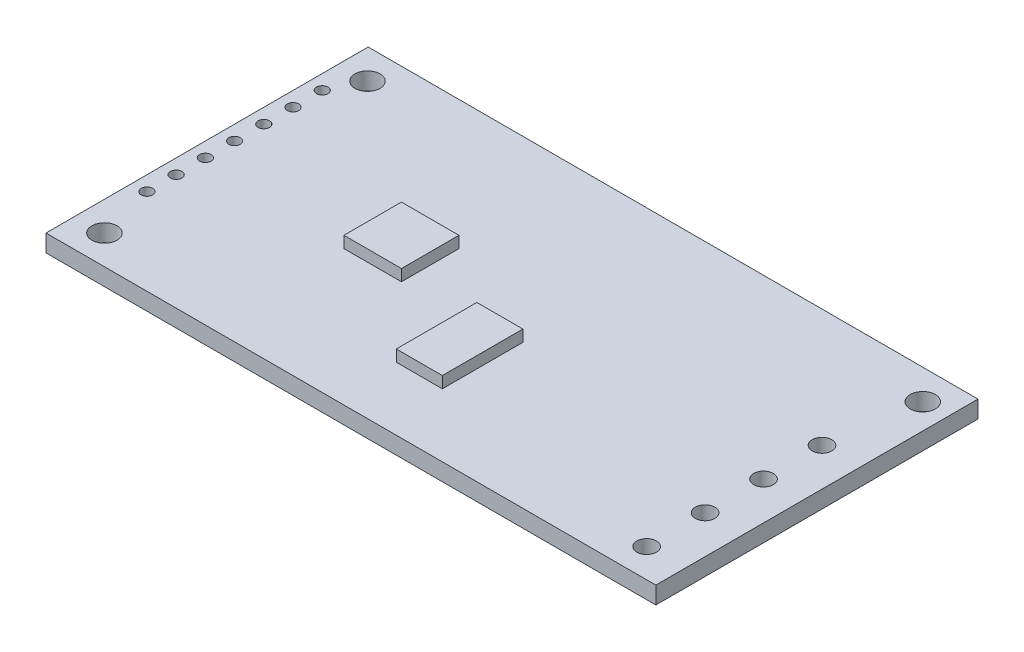
SolidWorks part; units mm, degrees
material "A-Glass Fiber"
ref_plane "Front Plane" through (0, 0, 0) normal (0, 0, 1) x (1, 0, 0)
ref_plane "Top Plane" through (0, 0, 0) normal (0, 1, 0) x (1, 0, 0)
ref_plane "Right Plane" through (0, 0, 0) normal (1, 0, 0) x (0, 0, -1)
sketch "Sketch1" plane through (0, 0, 0) normal (0, 1, 0) x (1, 0, 0)
  line L1 (-26.5, -14) -> (26.5, -14)
  line L2 (-26.5, -14) -> (-26.5, 14)
  line L3 (-26.5, 14) -> (26.5, 14)
  line L4 (26.5, -14) -> (26.5, 14)
  line L5 (-26.5, -14) -> (26.5, 14) construction
  line L6 (-26.5, 14) -> (26.5, -14) construction
  point P0 (0, 0)
  dimension "D1" = 53
  dimension "D2" = 28
extrude "Boss-Extrude1" add sketch "Sketch1" along normal blind 1.5
sketch "Sketch2" plane through (0, 1.5, 0) normal (0, 1, 0) x (1, 0, 0)
  line L0 (-26.5, 14) -> (-26.5, -14) construction
  line L1 (-26.5, -14) -> (26.5, -14) construction
  circle A0 centre (-23.96, -11.46) radius 1.0922
  dimension "D1" = 2.1844
  dimension "D2" = 2.54
  dimension "D3" = 2.54
extrude "Cut-Extrude1" cut sketch "Sketch2" against normal through all
pattern_linear "LPattern1" count 2 spacing 22.86 along (0, 0, -1) count 2 spacing 48.26 along (1, 0, 0) skipping (0, 1) of "Cut-Extrude1"
sketch "Sketch3" plane through (0, 1.5, 0) normal (0, 1, 0) x (1, 0, 0)
  line L0 (-26.5, 14) -> (-26.5, -14) construction
  circle A0 centre (-25.23, 8.7398) radius 0.5
  dimension "D1" = 1
  dimension "D2" = 1.27
extrude "Cut-Extrude2" cut sketch "Sketch3" against normal through all
pattern_linear "LPattern2" count 7 spacing 2.54 along (0, 0, 1) of "Cut-Extrude2"
sketch "Sketch5" plane through (0, 1.5, 0) normal (0, 1, 0) x (1, 0, 0)
  line L0 (-26.5, -14) -> (26.5, -14) construction
  line L1 (26.5, -14) -> (26.5, 14) construction
  circle A0 centre (23.2, -11.5) radius 0.85
  dimension "D1" = 2.5
  dimension "D2" = 3.3
extrude "Cut-Extrude3" cut sketch "Sketch5" against normal through all
pattern_linear "LPattern4" count 4 spacing 5.08 along (0, 0, -1) of "Cut-Extrude3"
sketch "Sketch6" plane through (0, 1.5, 0) normal (0, 1, 0) x (1, 0, 0)
  line L1 (-12.3816, 2.7728) -> (-7.3816, 2.7728)
  line L2 (-12.3816, 2.7728) -> (-12.3816, -2.2272)
  line L3 (-12.3816, -2.2272) -> (-7.3816, -2.2272)
  line L4 (-7.3816, 2.7728) -> (-7.3816, -2.2272)
  line L5 (-12.3816, 2.7728) -> (-7.3816, -2.2272) construction
  line L6 (-12.3816, -2.2272) -> (-7.3816, 2.7728) construction
  line L7 (-1.5494, -1.5045) -> (2.4506, -1.5045)
  line L8 (-1.5494, -1.5045) -> (-1.5494, -8.5045)
  line L9 (-1.5494, -8.5045) -> (2.4506, -8.5045)
  line L10 (2.4506, -1.5045) -> (2.4506, -8.5045)
  line L11 (-1.5494, -1.5045) -> (2.4506, -8.5045) construction
  line L12 (-1.5494, -8.5045) -> (2.4506, -1.5045) construction
  point P0 (-9.8816, 0.2728)
  point P5 (0.4506, -5.0045)
extrude "Boss-Extrude3" add sketch "Sketch6" along normal blind 1
